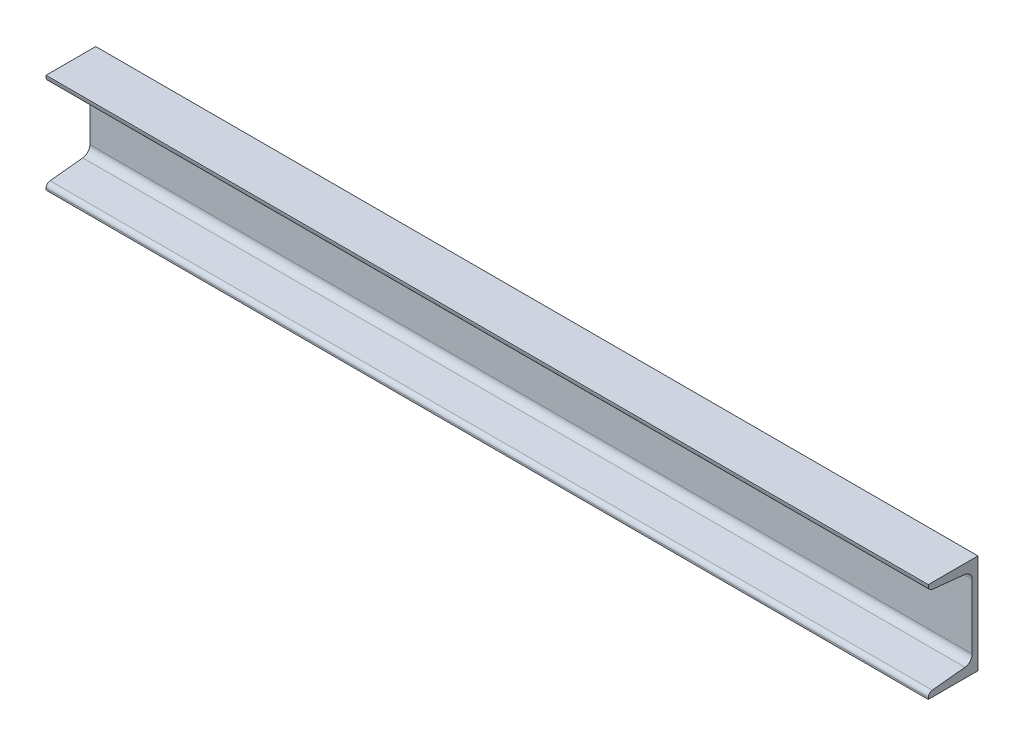
SolidWorks part; units mm, degrees
ref_plane "Front Plane" through (0, 0, 0) normal (0, 0, 1) x (1, 0, 0)
ref_plane "Top Plane" through (0, 0, 0) normal (0, 1, 0) x (1, 0, 0)
ref_plane "Right Plane" through (0, 0, 0) normal (1, 0, 0) x (0, 0, -1)
sketch "Sketch1" plane through (0, 0, 0) normal (0, 1, 0) x (1, 0, 0)
  line L0 (0, 0) -> (-887, 0)
  dimension "D1" = 887
other "C channel 100 X 10(1)"
ref_plane "Plane2" through (0, 0, 0) normal (-1, 0, 0) x (0, 0, 1)
sketch "Sketch13" plane through (0, 0, 0) normal (-1, 0, 0) x (0, 0, 1)
  line L0 (50, 100) -> (0, 100)
  line L1 (50, 0) -> (0, 0)
  line L2 (0, 100) -> (0, 0)
  line L6 (50, 100) -> (50, 98.3701)
  line L7 (50, 0) -> (50, 1.6299)
  line L12 (5.9, 82.48) -> (5.9, 17.52)
  line L17 (13.0638, 90.4362) -> (45.9704, 93.8948)
  line L18 (13.0638, 9.5638) -> (45.9704, 6.1052)
  arc A0 (45.9704, 93.8948) -> (50, 98.3701) centre (45.5, 98.3701) ccw
  arc A1 (45.9704, 6.1052) -> (50, 1.6299) centre (45.5, 1.6299) cw
  arc A9 (5.9, 17.52) -> (13.0638, 9.5638) centre (13.9, 17.52) ccw
  arc A10 (5.9, 82.48) -> (13.0638, 90.4362) centre (13.9, 82.48) cw
  point P8 (0, 50)
  point P9 (5.9, 50)
  point P10 (25, 100)
  point P11 (25, 0)
  point P12 (50, 5.6817)
  point P13 (50, 94.3183)
  point P14 (0, 0)
  dimension "D4" = 4.5
  dimension "RI" = 8
  dimension "D2" = 6
  dimension "D3" = 17.52
  dimension "Depth" = 100
  dimension "BF" = 50
  dimension "TW" = 5.9
  dimension "d1" = 64.96
ref_plane "Plane3" through (0, 50, 0) normal (0, -1, 0) x (-1, 0, 0)
